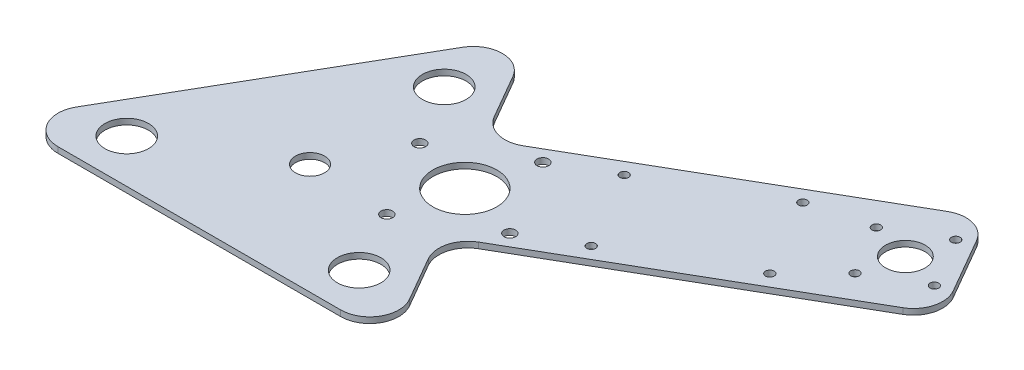
SolidWorks part; units mm, degrees
ref_plane "Front Plane" through (0, 0, 0) normal (0, 0, 1) x (1, 0, 0)
ref_plane "Top Plane" through (0, 0, 0) normal (0, 1, 0) x (1, 0, 0)
ref_plane "Right Plane" through (0, 0, 0) normal (1, 0, 0) x (0, 0, -1)
sketch "Sketch1" plane through (0, 0, 0) normal (0, 1, 0) x (1, 0, 0)
  line L0 (0, 0) -> (0, 85.65) construction
  line L1 (0, 0) -> (-86.4758, -49.9268) construction
  line L2 (0, 0) -> (78.7364, -45.4585) construction
  line L3 (0, 46.188) -> (-40, -23.094) construction
  line L4 (-40, -23.094) -> (40, -23.094) construction
  line L5 (40, -23.094) -> (0, 46.188) construction
  line L6 (0, 76.188) -> (-65.9808, -38.094)
  line L7 (-65.9808, -38.094) -> (65.9808, -38.094)
  line L8 (65.9808, -38.094) -> (0, 76.188)
  circle A0 centre (0, 46.188) radius 7.5
  circle A1 centre (-40, -23.094) radius 7.5
  circle A2 centre (40, -23.094) radius 7.5
  circle A3 centre (0, 0) radius 5
  dimension "D6" = 15
  dimension "D8" = 10
  dimension "D1" = 120
  dimension "D2" = 120
  dimension "D3" = 80
  dimension "D4" = 80
  dimension "D5" = 80
  dimension "D7" = 15
extrude "Boss-Extrude1" add sketch "Sketch1" along normal blind 2
sketch "Sketch2" plane through (0, 2, 0) normal (0, 1, 0) x (1, 0, 0)
  line L0 (-65.9808, -38.094) -> (-40, -23.094) construction
  line L1 (-40, -23.094) -> (205.1906, 118.4669) construction
  line L2 (43.4904, 0.8605) -> (22.4904, 37.2335)
  line L3 (43.4904, 0.8605) -> (153.3942, 64.3135)
  line L4 (22.4904, 37.2335) -> (132.3942, 100.6865)
  line L5 (153.3942, 64.3135) -> (132.3942, 100.6865)
  line L6 (65.9808, -38.094) -> (0, 76.188) construction
  dimension "D1" = 165
  dimension "D2" = 21
  dimension "D3" = 21
extrude "Boss-Extrude2" add sketch "Sketch2" against normal blind 2
fillet "Fillet1" radius 10 7 edges at (132.3942, 1, -100.6865) (153.3942, 1, -64.3135) (22.4904, 1, -37.2335) (43.4904, 1, -0.8605) (0, 1, -76.188) (65.9808, 1, 38.094) (-65.9808, 1, 38.094)
sketch "Sketch4" plane through (0, 2, 0) normal (0, 1, 0) x (1, 0, 0)
  line L4 (52.1506, 5.8605) -> (144.7339, 59.3135) construction
  line L5 (123.7339, 95.6865) -> (31.1506, 42.2335) construction
  line L6 (26.0885, -9.1865) -> (41.4615, 48.1865) construction
  line L7 (62.4615, 11.8135) -> (5.0885, 27.1865) construction
  line L8 (12.6016, 25.1734) -> (39.4484, 40.6734) construction
  line L9 (39.4484, 40.6734) -> (54.9484, 13.8266) construction
  line L10 (54.9484, 13.8266) -> (28.1016, -1.6734) construction
  line L11 (28.1016, -1.6734) -> (12.6016, 25.1734) construction
  circle A0 centre (33.775, 19.5) radius 11
  circle A1 centre (39.4484, 40.6734) radius 2
  circle A2 centre (54.9484, 13.8266) radius 2
  circle A3 centre (28.1016, -1.6734) radius 2
  circle A4 centre (12.6016, 25.1734) radius 2
  dimension "D3" = 22
  dimension "D5" = 4
  dimension "D1" = 42
  dimension "D4" = 31
extrude "Cut-Extrude1" cut sketch "Sketch4" against normal blind 2
sketch "Sketch6" plane through (0, 2, 0) normal (0, 1, 0) x (1, 0, 0)
  line L0 (114.1518, 102.2833) -> (147.5931, 44.3613) construction
  line L1 (142.8942, 82.5) -> (96.9715, 55.9865) construction
  line L2 (148.3942, 72.9737) -> (137.3942, 92.0263) construction
  circle A0 centre (129.9038, 75) radius 6.8
  point P6 (129.9038, 75)
  dimension "D2" = 13.6
  dimension "D1" = 15
extrude "Cut-Extrude2" cut sketch "Sketch6" against normal blind 10
sketch "Sketch8" plane through (0, 2, 0) normal (0, 1, 0) x (1, 0, 0)
  circle A0 centre (133.5641, 88.6603) radius 1.5
  circle A1 centre (143.5641, 71.3397) radius 1.5
  circle A2 centre (126.2436, 61.3397) radius 1.5
  circle A3 centre (116.2436, 78.6603) radius 1.5
  dimension "D5" = 3
extrude "Cut-Extrude3" cut sketch "Sketch8" against normal through all
sketch "Sketch9" plane through (0, 2, 0) normal (0, 1, 0) x (1, 0, 0)
  line L0 (39.4484, 40.6734) -> (115.053, 84.3238) construction
  line L1 (123.7339, 95.6865) -> (31.1506, 42.2335) construction
  line L2 (54.9484, 13.8266) -> (137.7228, 61.6164) construction
  line L3 (52.1506, 5.8605) -> (144.7339, 59.3135) construction
  line L4 (148.3942, 72.9737) -> (137.3942, 92.0263) construction
  circle A0 centre (57.2019, 50.9234) radius 1.5
  circle A1 centre (72.7019, 24.0766) radius 1.5
  circle A2 centre (111.673, 46.5766) radius 1.5
  circle A3 centre (96.173, 73.4234) radius 1.5
  dimension "D3" = 3
  dimension "D4" = 3
  dimension "D7" = 3
  dimension "D8" = 3
  dimension "D1" = 45
  dimension "D2" = 45
  dimension "D5" = 90
  dimension "D6" = 90
extrude "Cut-Extrude4" cut sketch "Sketch9" against normal blind 10
